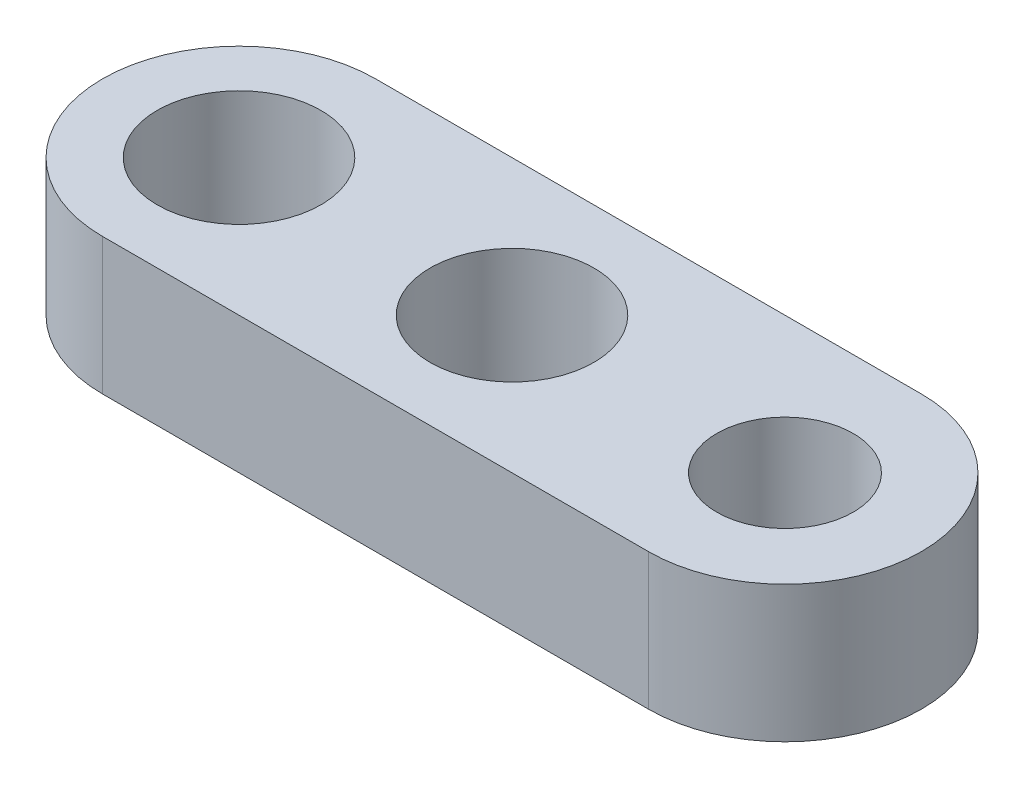
SolidWorks part; units mm, degrees
ref_plane "Front Plane" through (0, 0, 0) normal (0, 0, 1) x (1, 0, 0)
ref_plane "Top Plane" through (0, 0, 0) normal (0, 1, 0) x (1, 0, 0)
ref_plane "Right Plane" through (0, 0, 0) normal (1, 0, 0) x (0, 0, -1)
sketch "Sketch1" plane through (0, 0, 0) normal (0, 1, 0) x (1, 0, 0)
  line L0 (0, 0) -> (-20, 0) construction
  line L1 (0, -5) -> (-20, -5)
  line L2 (0, 5) -> (-20, 5)
  arc A0 (0, -5) -> (0, 5) centre (0, 0) ccw
  arc A1 (-20, 5) -> (-20, -5) centre (-20, 0) ccw
  circle A2 centre (0, 0) radius 2.5
  circle A3 centre (-20, 0) radius 3
  circle A4 centre (-10, 0) radius 3
  point P3 (-10, 0)
  dimension "D1" = 5
  dimension "D4" = 6
  dimension "D5" = 6
  dimension "D2" = 20
  dimension "D3" = 10
extrude "Boss-Extrude1" add sketch "Sketch1" along normal blind 5
